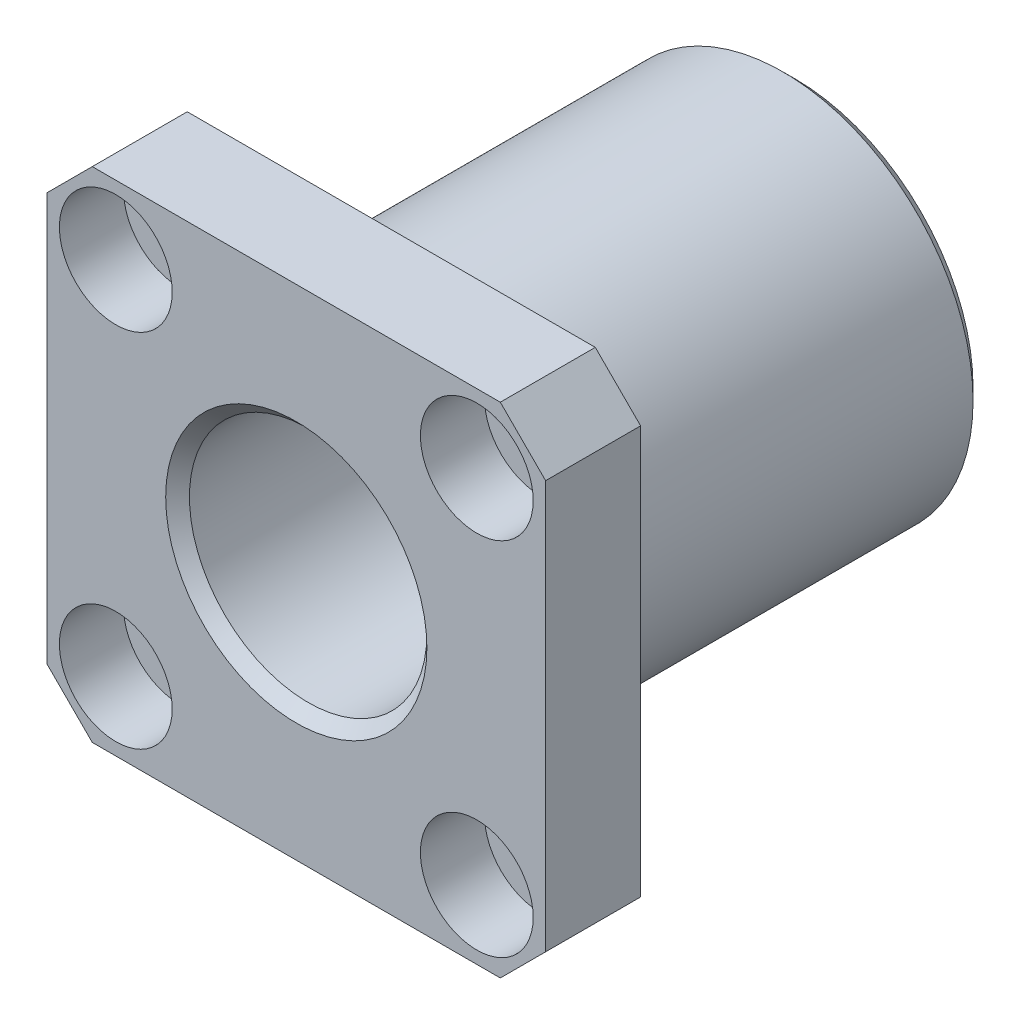
SolidWorks part; units mm, degrees
ref_plane "Front Plane" through (0, 0, 0) normal (0, 0, 1) x (1, 0, 0)
ref_plane "Top Plane" through (0, 0, 0) normal (0, 1, 0) x (1, 0, 0)
ref_plane "Right Plane" through (0, 0, 0) normal (1, 0, 0) x (0, 0, -1)
sketch "Sketch1" plane through (0, 0, 0) normal (0, 0, 1) x (1, 0, 0)
  circle A0 centre (0, 0) radius 16
  dimension "D1" = 32
extrude "Boss-Extrude1" add sketch "Sketch1" along normal blind 42
sketch "Sketch2" plane through (0, 0, 42) normal (0, 0, 1) x (1, 0, 0)
  line L1 (-21, -21) -> (21, -21)
  line L2 (-21, -21) -> (-21, 21)
  line L3 (-21, 21) -> (21, 21)
  line L4 (21, -21) -> (21, 21)
  line L5 (-21, -21) -> (21, 21) construction
  line L6 (-21, 21) -> (21, -21) construction
  point P0 (0, 0)
  dimension "D1" = 42
extrude "Boss-Extrude2" add sketch "Sketch2" against normal blind 8
sketch "Sketch4" plane through (0, 0, 42) normal (0, 0, 1) x (1, 0, 0)
  line L0 (0, 21) -> (0, -21) construction
  line L1 (21, 21) -> (-21, 21) construction
  line L2 (-21, -21) -> (21, -21) construction
  line L3 (-21, 21) -> (-21, 17.1838)
  line L4 (-21, 21) -> (-21, -21) construction
  line L5 (-21, 17.1838) -> (-17.1838, 21)
  line L6 (-17.1838, 21) -> (-21, 21)
  line L7 (17.1838, 21) -> (21, 21)
  line L8 (21, 17.1838) -> (17.1838, 21)
  line L9 (21, 21) -> (21, 17.1838)
  line L10 (-21, 0) -> (21, 0) construction
  line L11 (21, -21) -> (21, 21) construction
  line L12 (21, -21) -> (21, -17.1838)
  line L13 (21, -17.1838) -> (17.1838, -21)
  line L14 (17.1838, -21) -> (21, -21)
  line L15 (-17.1838, -21) -> (-21, -21)
  line L16 (-21, -17.1838) -> (-17.1838, -21)
  line L17 (-21, -21) -> (-21, -17.1838)
  dimension "D1" = 54
extrude "Cut-Extrude1" cut sketch "Sketch4" against normal through all
sketch "Sketch5" plane through (0, 0, 42) normal (0, 0, 1) x (1, 0, 0)
  line L0 (0, 0) -> (-19.0919, 19.0919) construction
  line L1 (-21, 17.1838) -> (-17.1838, 21) construction
  circle A0 centre (0, 0) radius 21.5 construction
  point P6 (-15.2028, 15.2028)
  point P10 (15.2028, 15.2028)
  point P11 (15.2028, -15.2028)
  point P12 (-15.2028, -15.2028)
  point P13 (0, 0)
  dimension "D1" = 43
  dimension "D2" = 4
hole_wizard "CBORE for M5 Hex Socket Head Cap Screw1" positions "Sketch6" profile "Sketch7" counterbore size "M5" standard "ISO"
sketch "Sketch6" plane through (0, 0, 42) normal (0, 0, 1) x (1, 0, 0)
  point P0 (-15.2028, 15.2028)
  point P3 (15.2028, 15.2028)
  point P6 (15.2028, -15.2028)
  point P9 (-15.2028, -15.2028)
sketch "Sketch7" plane through (-15.2028, 15.2028, 42) normal (1, 0, 0) x (0, -1, 0)
  line L0 (0, 0) -> (0, 23.6524)
  line L1 (0, 23.6524) -> (2.75, 22)
  line L2 (2.75, 22) -> (2.75, 5.4)
  line L3 (2.75, 5.4) -> (4.75, 5.4)
  line L4 (4.75, 5.4) -> (4.75, 0)
  line L5 (4.75, 0) -> (0, 0)
  line L10 (0, 23.6524) -> (-2.75, 22) construction
  line L11 (0, -6.35) -> (0, 107.95) construction
  dimension "Hole Dia." = 5.5
  dimension "Hole Depth" = 22
  dimension "C'Bore Dia." = 9.5
  dimension "C'Bore Depth" = 5.4
  dimension "Drill Angle" = 118
sketch "Sketch8" plane through (0, 0, 42) normal (0, 0, 1) x (1, 0, 0)
  circle A0 centre (0, 0) radius 10
  dimension "D1" = 20
extrude "Cut-Extrude2" cut sketch "Sketch8" against normal through all
chamfer "Chamfer1" distance 1 angle 45 2 edges at (16, 0, 0) (10, 0, 42)
